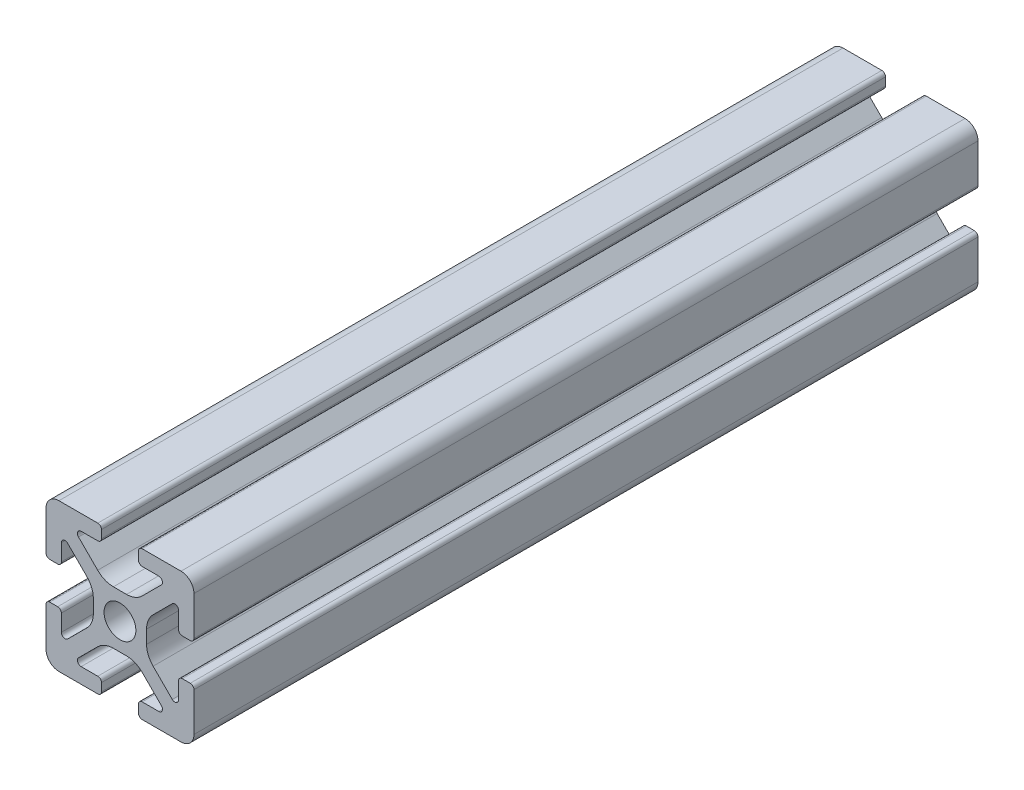
SolidWorks part; units mm, degrees
ref_plane "Front Plane" through (0, 0, 0) normal (0, 0, 1) x (1, 0, 0)
ref_plane "Top Plane" through (0, 0, 0) normal (0, 1, 0) x (1, 0, 0)
ref_plane "Right Plane" through (0, 0, 0) normal (1, 0, 0) x (0, 0, -1)
sketch "Sketch2" plane through (0, 0, 0) normal (0, 0, 1) x (1, 0, 0)
  line L0 (0, 10) -> (0, -10) construction
  line L1 (-10, 0) -> (10, 0) construction
  line L2 (2.5, -10) -> (10, -10)
  line L3 (10, -10) -> (10, -2.5)
  line L4 (2.5, -10) -> (2.5, -7.9246)
  line L5 (2.5, -7.9246) -> (6.4571, -7.9246)
  line L6 (6.4571, -7.9246) -> (2.1325, -3.6)
  line L7 (0, 0) -> (10, -10) construction
  line L8 (10, -2.5) -> (7.9246, -2.5)
  line L9 (7.9246, -2.5) -> (7.9246, -6.4571)
  line L10 (7.9246, -6.4571) -> (3.6, -2.1325)
  line L11 (5.7623, -4.2948) -> (4.2948, -5.7623) construction
  circle A0 centre (0, 0) radius 2.15
  arc A1 (5.25, -7.9246) -> (5.6036, -7.0711) centre (5.25, -7.4246) ccw construction
  point P8 (0, -3.6)
  point P16 (5.0286, -5.0286)
  dimension "Center Hole Diameter" = 4.3
  dimension "D3" = 0.5
  dimension "Rail Height" = 20
  dimension "Rail Width" = 20
  dimension "T-Slot Width" = 5
  dimension "Slot Depth" = 6.4
  dimension "Slot Inner Width" = 11.5
sketch "Sketch3" plane through (0, 0, 0) normal (1, 0, 0) x (0, 0, -1)
  line L0 (-304.8, -10) -> (304.8, -10) construction
  line L1 (-279.4, 0) -> (279.4, 0) construction
  line L2 (0, 10) -> (0, -10) construction
  line L3 (0, 10) -> (0, -10) construction
  point P6 (-279.4, 0)
  point P8 (279.4, 0)
  dimension "Length" = 609.6
  dimension "D1" = 25.4
sketch "Sketch4" plane through (0, 0, 0) normal (0, 0, 1) x (1, 0, 0)
  line L0 (3, -10) -> (8.25, -10)
  line L1 (2.5, -10) -> (10, -10) construction
  line L2 (2.5, -10) -> (2.5, -7.9246) construction
  line L3 (2.5, -7.9246) -> (6.4571, -7.9246) construction
  line L4 (2.5, -8.4246) -> (2.5, -9.5)
  line L5 (3, -7.9246) -> (5.25, -7.9246)
  line L6 (0, -3.6) -> (0.8898, -3.6)
  line L7 (6.4571, -7.9246) -> (2.1325, -3.6) construction
  line L8 (3.0112, -4.4787) -> (5.6036, -7.0711)
  line L9 (10, -10) -> (10, -2.5) construction
  line L10 (7.9246, -6.4571) -> (3.6, -2.1325) construction
  line L11 (7.9246, -2.5) -> (7.9246, -6.4571) construction
  line L12 (7.9246, -5.25) -> (7.9246, -3)
  line L13 (10, -2.5) -> (7.9246, -2.5) construction
  line L14 (8.4246, -2.5) -> (9.5, -2.5)
  line L15 (10, -3) -> (10, -8.25)
  line L16 (7.0711, -5.6036) -> (4.4787, -3.0112)
  line L17 (3.6, 0) -> (3.6, -0.8898)
  line L18 (-10, 0) -> (10, 0) construction
  line L19 (0, -3.6) -> (0, -2.15)
  line L20 (0, 10) -> (0, -10) construction
  line L21 (3.6, 0) -> (2.15, 0)
  arc A0 (2.5, -9.5) -> (3, -10) centre (3, -9.5) ccw
  arc A1 (5.25, -7.9246) -> (5.6036, -7.0711) centre (5.25, -7.4246) ccw construction
  arc A2 (2.5, -8.4246) -> (3, -7.9246) centre (3, -8.4246) cw
  arc A3 (5.25, -7.9246) -> (5.6036, -7.0711) centre (5.25, -7.4246) ccw
  arc A4 (0.8898, -3.6) -> (3.0112, -4.4787) centre (0.8898, -6.6) cw
  arc A5 (8.25, -10) -> (10, -8.25) centre (8.25, -8.25) ccw
  arc A6 (7.0711, -5.6036) -> (7.9246, -5.25) centre (7.4246, -5.25) ccw
  arc A7 (7.9246, -3) -> (8.4246, -2.5) centre (8.4246, -3) cw
  arc A8 (9.5, -2.5) -> (10, -3) centre (9.5, -3) cw
  arc A9 (4.4787, -3.0112) -> (3.6, -0.8898) centre (6.6, -0.8898) cw
  circle A10 centre (0, 0) radius 2.15 construction
  arc A11 (0, -2.15) -> (2.15, 0) centre (0, 0) ccw
  dimension "D1" = 1.75
  dimension "D2" = 3
extrude "Boss-Extrude1" add sketch "Sketch4" along normal mid plane 609.6
mirror "Mirror1" about plane through (0, 0, 0) normal (1, 0, 0) of bodies 134
mirror "Mirror2" about plane through (0, 0, 0) normal (0, 1, 0) of bodies 135
sketch "Sketch5" plane through (0, 0, -304.8) normal (0, 0, -1) x (-1, 0, 0)
  line L1 (-13.8311, 12.3183) -> (13.1641, 12.3183)
  line L2 (-13.8311, 12.3183) -> (-13.8311, -12.3688)
  line L3 (-13.8311, -12.3688) -> (13.1641, -12.3688)
  line L4 (13.1641, 12.3183) -> (13.1641, -12.3688)
extrude "Cut-Extrude1" cut sketch "Sketch5" against normal blind 503.6
equation "\"D3@Sketch2\"=\"T-Slot Width@Sketch2\"*0.1"
equation "\"D1@Sketch4\"=\"D3@Sketch2\"*3.5"
equation "\"D2@Sketch4\"=\"D3@Sketch2\"*6"
equation "\"D1@Boss-Extrude1\"=\"Length@Sketch3\""
